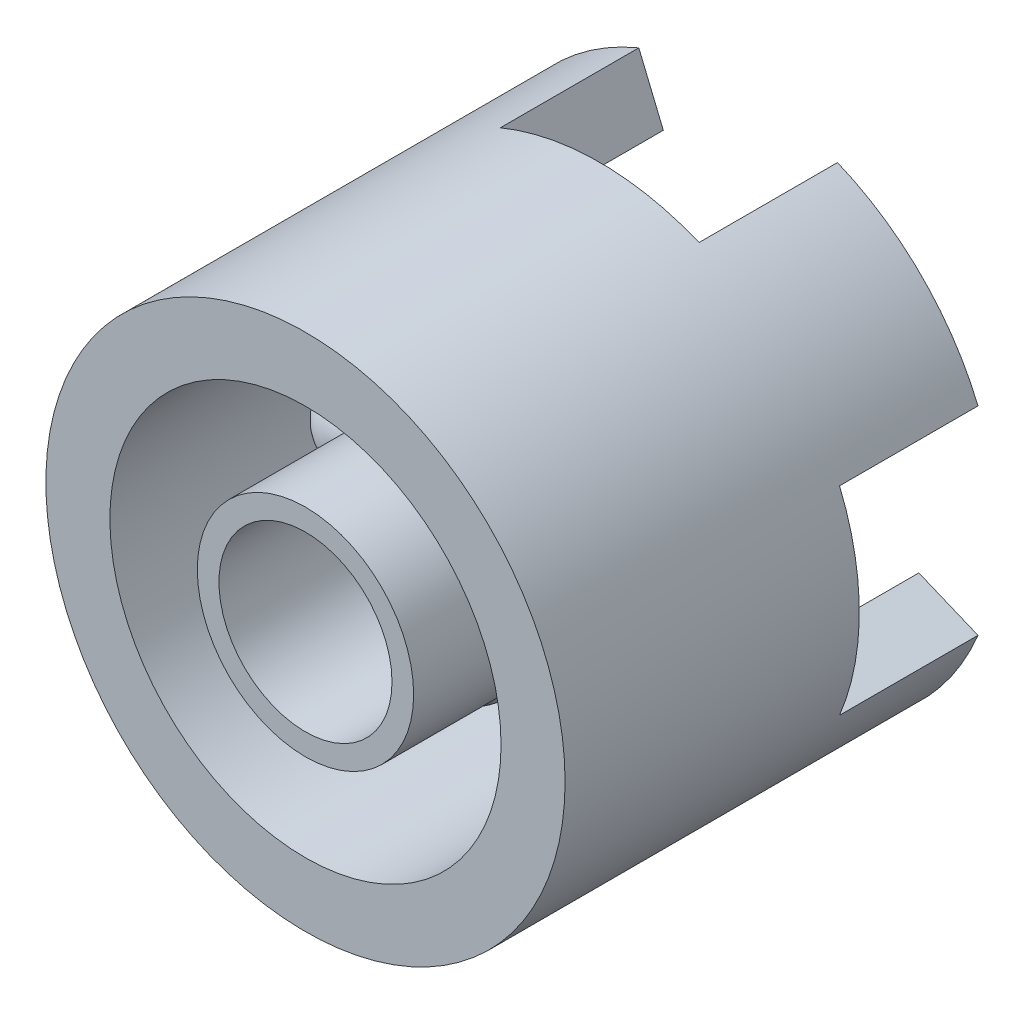
SolidWorks part; units mm, degrees
ref_plane "Front Plane" through (0, 0, 0) normal (0, 0, 1) x (1, 0, 0)
ref_plane "Top Plane" through (0, 0, 0) normal (0, 1, 0) x (1, 0, 0)
ref_plane "Right Plane" through (0, 0, 0) normal (1, 0, 0) x (0, 0, -1)
sketch "Sketch1" plane through (0, 0, 0) normal (0, 0, 1) x (1, 0, 0)
  circle A0 centre (0, 0) radius 19.05
  circle A1 centre (0, 0) radius 14.351
  circle A2 centre (0, 0) radius 7.9375
  circle A3 centre (0, 0) radius 6.35
  dimension "D1" = 12.7
  dimension "D2" = 38.1
  dimension "D3" = 28.702
  dimension "D4" = 15.875
extrude "Boss-Extrude1" add sketch "Sketch1" along normal blind 31.75 contours A0 A1 | A2 A3
sketch "Sketch2" plane through (0, 0, 0) normal (0, 1, 0) x (1, 0, 0)
  line L0 (7.874, -15.875) -> (14.224, -15.875)
  line L1 (0, 0) -> (0, -31.75)
  line L2 (-6.35, -31.75) -> (6.35, -31.75) construction
  line L3 (-18.8665, -15.875) -> (18.8665, -15.875)
  line L4 (11.049, -31.75) -> (11.049, 0)
  line L5 (14.351, 0) -> (-14.351, 0) construction
  line L6 (-14.351, -31.75) -> (14.351, -31.75) construction
  arc A0 (14.224, -15.875) -> (7.874, -15.875) centre (11.049, -15.875) ccw
  point P1 (0, -15.875)
  point P15 (11.2322, -31.75)
  point P18 (0, 0)
  point P19 (15.0055, -15.875)
  point P20 (0, 0)
  point P21 (0, 0)
  point P22 (0, 0)
  point P23 (0, 0)
  point P24 (0, 0)
  point P25 (0, 0)
  point P26 (0, 0)
  dimension "D1" = 6.35
  dimension "D2" = 11.049
revolve "Revolve1" add sketch "Sketch2" angle 360 about L0
pattern_circular "CirPattern1" count 10 over 360 about axis through (0, 0, 0) along (0, 0, 1) of "Revolve1"
sketch "Sketch3" plane through (0, 0, 0) normal (0, 0, -1) x (-1, 0, 0)
  line L2 (0, 0) -> (0, 14.351)
  line L3 (-7.2901, 17.5999) -> (-5.4919, 13.2586)
  line L4 (7.2901, 17.5999) -> (5.4919, 13.2586)
  line L5 (0, 0) -> (-9.6324, 23.2548) construction
  line L6 (0, 0) -> (8.801, 21.2474) construction
  line L7 (17.5999, 7.2901) -> (13.2586, 5.4919)
  line L8 (17.5999, -7.2901) -> (13.2586, -5.4919)
  line L9 (7.2901, -17.5999) -> (5.4919, -13.2586)
  line L10 (-7.2901, -17.5999) -> (-5.4919, -13.2586)
  line L11 (-17.5999, -7.2901) -> (-13.2586, -5.4919)
  line L12 (-17.5999, 7.2901) -> (-13.2586, 5.4919)
  arc A1 (13.2586, -5.4919) -> (13.2586, 5.4919) centre (0, 0) ccw
  circle A2 centre (0, 0) radius 14.351 construction
  arc A3 (5.4919, 13.2586) -> (-5.4919, 13.2586) centre (0, 0) ccw
  circle A4 centre (0, 0) radius 19.05 construction
  arc A5 (7.2901, 17.5999) -> (-7.2901, 17.5999) centre (0, 0) ccw
  arc A6 (17.5999, -7.2901) -> (17.5999, 7.2901) centre (0, 0) ccw
  arc A7 (-5.4919, -13.2586) -> (5.4919, -13.2586) centre (0, 0) ccw
  arc A8 (-7.2901, -17.5999) -> (7.2901, -17.5999) centre (0, 0) ccw
  arc A9 (-13.2586, 5.4919) -> (-13.2586, -5.4919) centre (0, 0) ccw
  arc A10 (-17.5999, 7.2901) -> (-17.5999, -7.2901) centre (0, 0) ccw
  point P28 (0, 0)
  dimension "D2" = 4
  dimension "D1" = 45
  dimension "D3" = 22.5
extrude "Cut-Extrude1" cut sketch "Sketch3" against normal blind 10.16 contours L11 A9 L12 A10 | L9 A7 L10 A8 | L7 A1 L8 A6 | L4 A3 L3 A5
